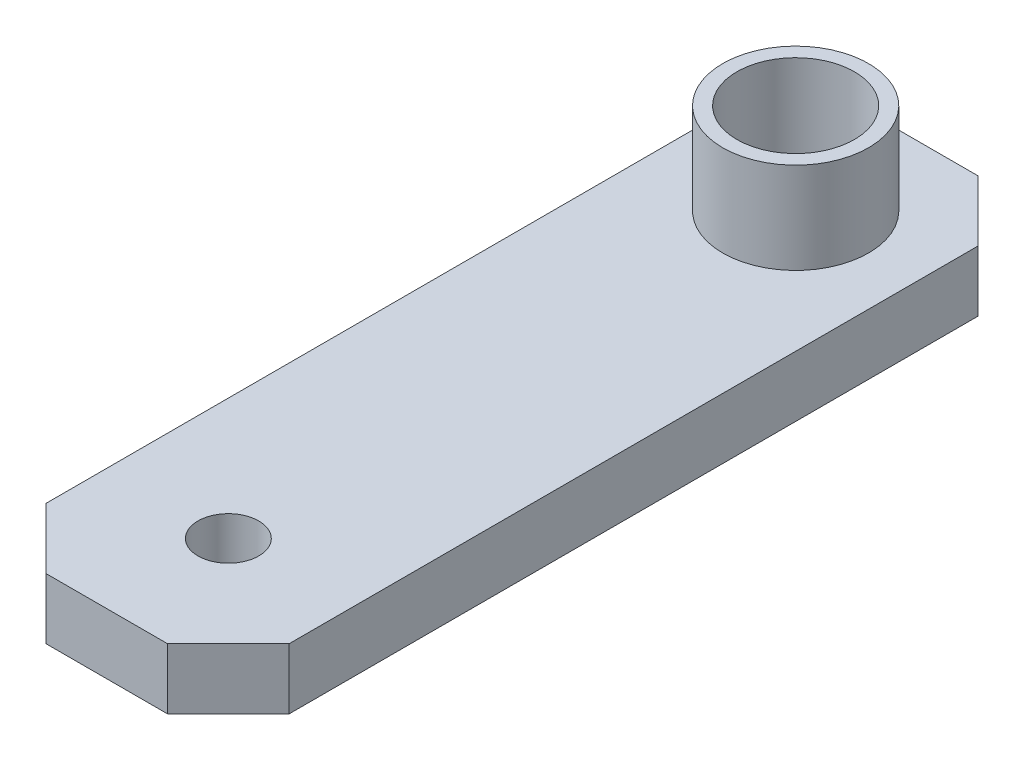
SolidWorks part; units mm, degrees
ref_plane "Front Plane" through (0, 0, 0) normal (0, 0, 1) x (1, 0, 0)
ref_plane "Top Plane" through (0, 0, 0) normal (0, 1, 0) x (1, 0, 0)
ref_plane "Right Plane" through (0, 0, 0) normal (1, 0, 0) x (0, 0, -1)
sketch "Sketch1" plane through (0, 0, 0) normal (0, 1, 0) x (1, 0, 0)
  line L0 (-6, 17) -> (-3, 20)
  line L1 (-3, 20) -> (3, 20)
  line L2 (-6, 17) -> (-6, -17)
  line L3 (-3, -20) -> (3, -20)
  line L4 (6, 17) -> (6, -17)
  line L5 (-6, 20) -> (6, -20) construction
  line L6 (-6, -20) -> (6, 20) construction
  line L7 (3, 20) -> (6, 17)
  line L8 (3, -20) -> (6, -17)
  line L9 (-6, -17) -> (-3, -20)
  circle A0 centre (0, 14) radius 1.5
  circle A1 centre (0, -14) radius 1.5
  point P0 (0, 0)
  dimension "D3" = 3
  dimension "D1" = 40
  dimension "D2" = 12
  dimension "D4" = 14
  dimension "D5" = 14
extrude "Boss-Extrude1" add sketch "Sketch1" along normal blind 3
sketch "Sketch2" plane through (0, 3, 0) normal (0, 1, 0) x (1, 0, 0)
  circle A0 centre (0, 14) radius 3.6
  circle A1 centre (0, 14) radius 2.9
  dimension "D1" = 5.8
  dimension "D2" = 7.2
extrude "Boss-Extrude2" add sketch "Sketch2" along normal blind 4.5
